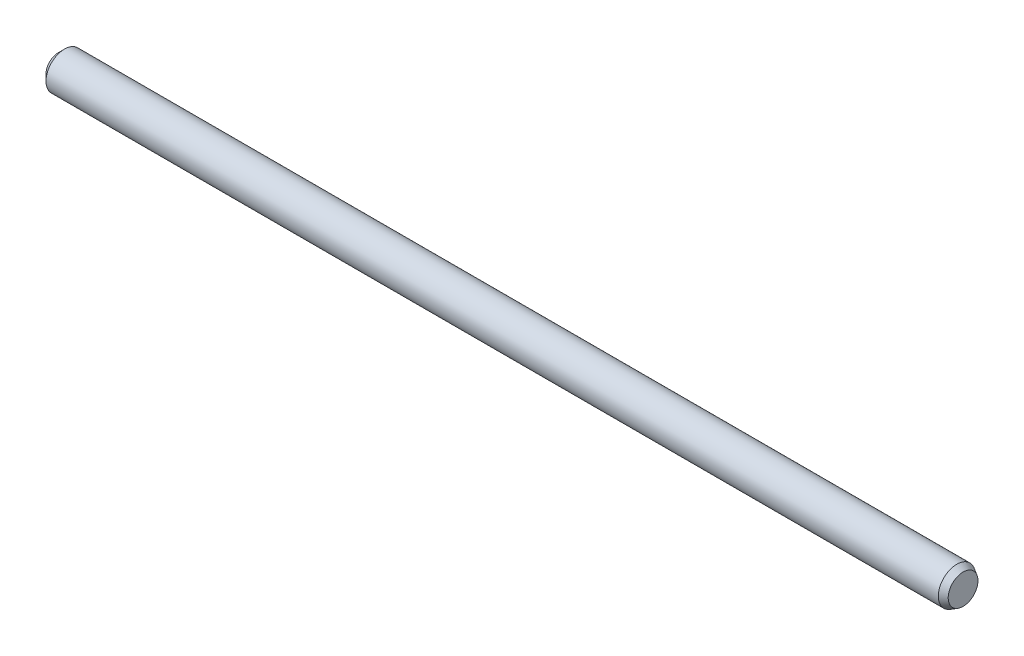
SolidWorks part; units mm, degrees
ref_plane "Alzado" through (0, 0, 0) normal (0, 0, 1) x (1, 0, 0)
ref_plane "Planta" through (0, 0, 0) normal (0, 1, 0) x (1, 0, 0)
ref_plane "Vista lateral" through (0, 0, 0) normal (1, 0, 0) x (0, 0, -1)
sketch "Croquis1" plane through (0, 0, 0) normal (1, 0, 0) x (0, 0, -1)
  circle A0 centre (0, 0) radius 1.475
  dimension "D1" = 2.95
extrude "Saliente-Extruir1" add sketch "Croquis1" along normal blind 72
chamfer "Chaflán1" distance 0.5 angle 30 1 edges at (72, 0, -1.475)
chamfer "Chaflán2" distance 0.5 angle 45 1 edges at (0, 0, -1.475)
